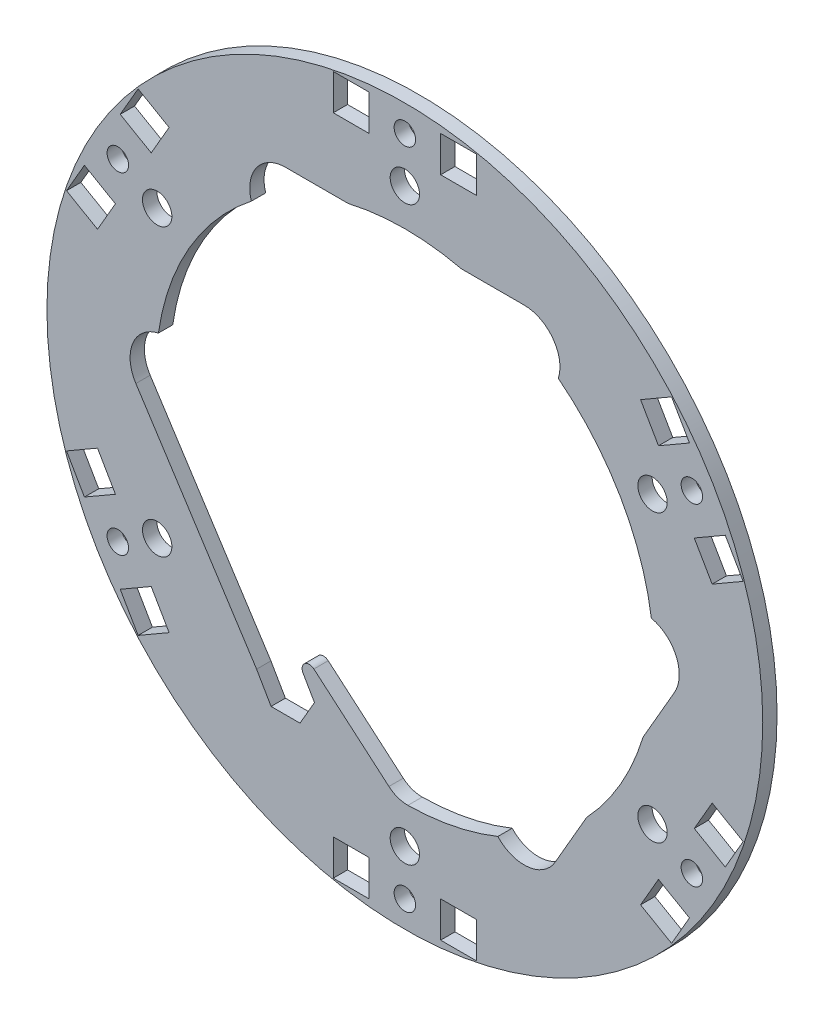
SolidWorks part; units mm, degrees
ref_plane "Plan de face" through (0, 0, 0) normal (0, 0, 1) x (1, 0, 0)
ref_plane "Plan de dessus" through (0, 0, 0) normal (0, 1, 0) x (1, 0, 0)
ref_plane "Plan de droite" through (0, 0, 0) normal (1, 0, 0) x (0, 0, -1)
sketch "Esquisse1" plane through (0, 0, 0) normal (0, 0, 1) x (1, 0, 0)
  line L0 (53.6751, 0) -> (-86.559, 0) construction
  line L1 (0, 50) -> (0, -56.2363) construction
  line L2 (0, 0) -> (70.5826, 40.7509) construction
  line L3 (0, 0) -> (-77.9761, 45.0195) construction
  line L4 (-33.3333, 0) -> (-16.6667, -28.8675) construction
  line L5 (-28.8394, 2.305) -> (-14.6459, -25.3675)
  line L6 (-37.5765, -2.7394) -> (-20.7081, -28.8675)
  line L7 (16.6667, -28.8675) -> (33.3333, 0) construction
  line L8 (12.3365, -26.3675) -> (29.0032, 2.5)
  line L9 (20.9968, -31.3675) -> (37.6635, -2.5)
  line L10 (-16.6667, 28.8675) -> (16.6667, 28.8675) construction
  line L11 (-16.6667, 33.8675) -> (16.6667, 33.8675)
  line L12 (-16.6667, 23.8675) -> (16.6667, 23.8675)
  line L15 (-20.7081, -28.8675) -> (-18.6874, -32.3675)
  line L16 (-18.6874, -32.3675) -> (-14.6459, -32.3675)
  line L17 (-14.6459, -32.3675) -> (-12.6252, -28.8675)
  line L18 (-12.6252, -28.8675) -> (-14.6459, -25.3675)
  line L20 (-14.6459, -25.3675) -> (-18.6874, -25.3675) [skipped]
  line L21 (-18.6874, -25.3675) -> (-20.7081, -28.8675) [skipped]
  circle A0 centre (0, 0) radius 50
  circle A1 centre (33.3333, 0) radius 16.6667 construction
  circle A2 centre (16.6667, -28.8675) radius 16.6667 construction
  circle A3 centre (-16.6667, -28.8675) radius 16.6667 construction
  circle A4 centre (-33.3333, 0) radius 16.6667 construction
  circle A5 centre (-16.6667, 28.8675) radius 16.6667 construction
  circle A6 centre (16.6667, 28.8675) radius 16.6667 construction
  circle A7 centre (-34.5978, 19.9751) radius 2.05
  circle A8 centre (0, 39.9502) radius 2.05
  circle A9 centre (34.5978, 19.9751) radius 2.05
  circle A10 centre (34.5978, -19.9751) radius 2.05
  circle A11 centre (0, -39.9502) radius 2.05
  circle A12 centre (-34.5978, -19.9751) radius 2.05
  circle A13 centre (0, 19.1653) radius 2.05
  circle A14 centre (0, 0) radius 16.6667 construction
  circle A15 centre (0, -19.2328) radius 2.05
  circle A17 centre (-16.6667, -28.8675) radius 3.5 construction
  circle A22 centre (0, 0) radius 2.05
  circle A23 centre (-16.6714, -9.6252) radius 2.05
  circle A24 centre (16.6696, 9.6242) radius 2.05
  circle A25 centre (-16.6714, 9.6252) radius 2.05
  circle A26 centre (16.6667, -9.6225) radius 2.05
  arc A27 (-28.8394, 2.305) -> (-37.5765, -2.7394) centre (-33.3333, 0) ccw
  arc A29 (12.3365, -26.3675) -> (20.9968, -31.3675) centre (16.6667, -28.8675) ccw
  arc A30 (37.6635, -2.5) -> (29.0032, 2.5) centre (33.3333, 0) ccw
  arc A31 (-16.6667, 33.8675) -> (-16.6667, 23.8675) centre (-16.6667, 28.8675) ccw
  arc A32 (16.6667, 23.8675) -> (16.6667, 33.8675) centre (16.6667, 28.8675) ccw
  point P20 (0, 0)
  point P30 (0, 0)
  point P54 (0, 0)
  point P60 (0, 0)
  point P64 (-25, -14.4338)
  point P69 (25, -14.4338)
  point P74 (0, 28.8675)
  line B0 (37.597, -27.4801) -> (42.597, -18.8199) construction
  line B1 (35.4319, -26.2301) -> (32.9319, -30.5603)
  line B2 (35.4319, -26.2301) -> (39.762, -28.7301)
  line B3 (39.762, -28.7301) -> (37.262, -33.0603)
  line B4 (32.9319, -30.5603) -> (37.262, -33.0603)
  line B5 (40.4319, -17.5699) -> (42.9319, -13.2397)
  line B6 (40.4319, -17.5699) -> (44.762, -20.0699)
  line B7 (44.762, -20.0699) -> (47.262, -15.7397)
  line B8 (42.9319, -13.2397) -> (47.262, -15.7397)
  circle B9 centre (40.097, -23.15) radius 1.5
  line B10 (-5, -46.3) -> (5, -46.3) construction
  line B11 (-5, -43.8) -> (-10, -43.8)
  line B12 (-5, -43.8) -> (-5, -48.8)
  line B13 (-5, -48.8) -> (-10, -48.8)
  line B14 (-10, -43.8) -> (-10, -48.8)
  line B15 (5, -43.8) -> (10, -43.8)
  line B16 (5, -43.8) -> (5, -48.8)
  line B17 (5, -48.8) -> (10, -48.8)
  line B18 (10, -43.8) -> (10, -48.8)
  circle B19 centre (0, -46.3) radius 1.5
  line B20 (-42.597, -18.8199) -> (-37.597, -27.4801) construction
  line B21 (-40.4319, -17.5699) -> (-42.9319, -13.2397)
  line B22 (-40.4319, -17.5699) -> (-44.762, -20.0699)
  line B23 (-44.762, -20.0699) -> (-47.262, -15.7397)
  line B24 (-42.9319, -13.2397) -> (-47.262, -15.7397)
  line B25 (-35.4319, -26.2301) -> (-32.9319, -30.5603)
  line B26 (-35.4319, -26.2301) -> (-39.762, -28.7301)
  line B27 (-39.762, -28.7301) -> (-37.262, -33.0603)
  line B28 (-32.9319, -30.5603) -> (-37.262, -33.0603)
  circle B29 centre (-40.097, -23.15) radius 1.5
  line B30 (-37.597, 27.4801) -> (-42.597, 18.8199) construction
  line B31 (-35.4319, 26.2301) -> (-32.9319, 30.5603)
  line B32 (-35.4319, 26.2301) -> (-39.762, 28.7301)
  line B33 (-39.762, 28.7301) -> (-37.262, 33.0603)
  line B34 (-32.9319, 30.5603) -> (-37.262, 33.0603)
  line B35 (-40.4319, 17.5699) -> (-42.9319, 13.2397)
  line B36 (-40.4319, 17.5699) -> (-44.762, 20.0699)
  line B37 (-44.762, 20.0699) -> (-47.262, 15.7397)
  line B38 (-42.9319, 13.2397) -> (-47.262, 15.7397)
  circle B39 centre (-40.097, 23.15) radius 1.5
  line B40 (5, 46.3) -> (-5, 46.3) construction
  line B41 (5, 43.8) -> (10, 43.8)
  line B42 (5, 43.8) -> (5, 48.8)
  line B43 (5, 48.8) -> (10, 48.8)
  line B44 (10, 43.8) -> (10, 48.8)
  line B45 (-5, 43.8) -> (-10, 43.8)
  line B46 (-5, 43.8) -> (-5, 48.8)
  line B47 (-5, 48.8) -> (-10, 48.8)
  line B48 (-10, 43.8) -> (-10, 48.8)
  circle B49 centre (0, 46.3) radius 1.5
  line B50 (42.597, 18.8199) -> (37.597, 27.4801) construction
  line B51 (40.4319, 17.5699) -> (42.9319, 13.2397)
  line B52 (40.4319, 17.5699) -> (44.762, 20.0699)
  line B53 (44.762, 20.0699) -> (47.262, 15.7397)
  line B54 (42.9319, 13.2397) -> (47.262, 15.7397)
  line B55 (35.4319, 26.2301) -> (32.9319, 30.5603)
  line B56 (35.4319, 26.2301) -> (39.762, 28.7301)
  line B57 (39.762, 28.7301) -> (37.262, 33.0603)
  line B58 (32.9319, 30.5603) -> (37.262, 33.0603)
  circle B59 centre (40.097, 23.15) radius 1.5
  dimension "D1" = 6
  dimension "D2" = 30
  dimension "D4" = 6
  dimension "D6" = 46.3
  dimension "D3" = 30
  dimension "D7" = 6
sketch_block_instance "Trou M3 plots 5mm-1"
sketch_block "Trou M3 plots 5mm" parameters "D2"=3, "D1"=5, "D3"=5, "D4"=10
sketch_block_instance "Trou M3 plots 5mm-3"
sketch_block_instance "Trou M3 plots 5mm-4"
sketch_block_instance "Trou M3 plots 5mm-5"
sketch_block_instance "Trou M3 plots 5mm-6"
sketch_block_instance "Trou M3 plots 5mm-7"
extrude "Boss.-Extru.1" add sketch "Esquisse1" along normal blind 2
sketch "Sketch3" plane through (0, 0, 2) normal (0, 0, 1) x (1, 0, 0)
  line L0 (53.6751, 0) -> (-86.559, 0) construction
  line L1 (-11, -4) -> (-10, -4)
  line L2 (-11, -4) -> (-11, 4)
  line L3 (-11, 4) -> (-10, 4)
  line L4 (-10, -4) -> (-10, 4)
  line L5 (0, 50) -> (0, -56.2363) construction
  line L6 (16.6667, 28.8675) -> (-16.6667, -28.8675) construction
  line L7 (-23.3333, 4) -> (-22.3333, 4)
  line L8 (-23.3333, 4) -> (-23.3333, -4)
  line L9 (-23.3333, -4) -> (-22.3333, -4)
  line L10 (-22.3333, 4) -> (-22.3333, -4)
  line L11 (-16.6667, 28.8675) -> (16.6667, -28.8675) construction
  line L12 (-13.2337, 23.9214) -> (-14.0997, 23.4214)
  line L13 (-14.0997, 23.4214) -> (-12.3497, 20.3903)
  line L14 (-12.3497, 20.3903) -> (-15.3808, 18.6403)
  line L15 (-15.3808, 18.6403) -> (-14.8808, 17.7742)
  line L16 (-14.8808, 17.7742) -> (-11.8497, 19.5242)
  line L17 (-11.8497, 19.5242) -> (-10.0997, 16.4932)
  line L18 (-10.0997, 16.4932) -> (-9.2337, 16.9932)
  line L19 (-9.2337, 16.9932) -> (-10.9837, 20.0242)
  line L20 (-10.9837, 20.0242) -> (-7.9526, 21.7742)
  line L21 (-7.9526, 21.7742) -> (-8.4526, 22.6403)
  line L22 (-8.4526, 22.6403) -> (-11.4837, 20.8903)
  line L23 (-11.4837, 20.8903) -> (-13.2337, 23.9214)
  line L24 (-16.2531, 17.5593) -> (-5.3419, 23.8588) construction
  line L25 (-14.6252, 25.3316) -> (-8.4936, 14.7114) construction
  line L26 (15.1308, 18.2073) -> (14.6308, 17.3412)
  line L27 (15.1308, 18.2073) -> (8.2026, 22.2073)
  line L28 (8.2026, 22.2073) -> (7.7026, 21.3412)
  line L29 (14.6308, 17.3412) -> (7.7026, 21.3412)
  line L30 (8.2026, -22.2073) -> (7.7026, -21.3412)
  line L31 (8.2026, -22.2073) -> (15.1308, -18.2073)
  line L32 (15.1308, -18.2073) -> (14.6308, -17.3412)
  line L33 (7.7026, -21.3412) -> (14.6308, -17.3412)
  line L34 (27.3333, -0.5) -> (27.3333, 0.5)
  line L35 (27.3333, 0.5) -> (23.8333, 0.5)
  line L36 (23.8333, 0.5) -> (23.8333, 4)
  line L37 (23.8333, 4) -> (22.8333, 4)
  line L38 (22.8333, 4) -> (22.8333, 0.5)
  line L39 (22.8333, 0.5) -> (19.3333, 0.5)
  line L40 (19.3333, 0.5) -> (19.3333, -0.5)
  line L41 (19.3333, -0.5) -> (22.8333, -0.5)
  line L42 (22.8333, -0.5) -> (22.8333, -4)
  line L43 (22.8333, -4) -> (23.8333, -4)
  line L44 (23.8333, -4) -> (23.8333, -0.5)
  line L45 (23.8333, -0.5) -> (27.3333, -0.5)
  line L46 (-14.0997, -23.4214) -> (-13.2337, -23.9214)
  line L47 (-13.2337, -23.9214) -> (-11.4837, -20.8903)
  line L48 (-11.4837, -20.8903) -> (-8.4526, -22.6403)
  line L49 (-8.4526, -22.6403) -> (-7.9526, -21.7742)
  line L50 (-7.9526, -21.7742) -> (-10.9837, -20.0242)
  line L51 (-10.9837, -20.0242) -> (-9.2337, -16.9932)
  line L52 (-9.2337, -16.9932) -> (-10.0997, -16.4932)
  line L53 (-10.0997, -16.4932) -> (-11.8497, -19.5242)
  line L54 (-11.8497, -19.5242) -> (-14.8808, -17.7742)
  line L55 (-14.8808, -17.7742) -> (-15.3808, -18.6403)
  line L56 (-15.3808, -18.6403) -> (-12.3497, -20.3903)
  line L57 (-12.3497, -20.3903) -> (-14.0997, -23.4214)
  line L58 (-21.8333, 14.2784) -> (-24.4284, 9.7836) construction
  line L59 (173205.0808, -100000) -> (-173283.0568, 100045.0195) construction
  text T0 "+"
  point P4 (-10, 0)
  point P36 (-8.2026, 22.2073)
  point P39 (-13.6667, 23.6714)
  point P51 (0, 0)
  point P75 (0, 0)
  point P85 (-23.3333, 0)
  dimension "D1" = 8
  dimension "D2" = 1
  dimension "D3" = 10
  dimension "D4" = 1
  dimension "D5" = 8
  dimension "D6" = 10
  dimension "D7" = 1
  dimension "D8" = 1
  dimension "D9" = 8
  dimension "D10" = 8
  dimension "D11" = 4
  dimension "D12" = 4
  dimension "D13" = 10
  dimension "D14" = 3
  dimension "D15" = 3
extrude "Cut-Extrude2" cut sketch "Sketch3" against normal blind 10
sketch "Sketch4" plane through (0, 0, 2) normal (0, 0, 1) x (1, 0, 0)
  circle A0 centre (16.6667, -9.6225) radius 9
  circle A1 centre (0, -19.245) radius 9
  circle A2 centre (-16.6667, -9.6225) radius 9
  circle A3 centre (-16.6667, 9.6225) radius 9
  circle A4 centre (0, 19.245) radius 9
  circle A5 centre (16.6667, 9.6225) radius 9
  circle A6 centre (0, 0) radius 9
  point P15 (0, 0)
  dimension "D1" = 6
sketch "Sketch5" plane through (0, 0, 2) normal (0, 0, 1) x (1, 0, 0)
  line L3 (-16.6429, -21.474) -> (-1.1196, -34.7596)
  line L5 (-14.6459, -25.3675) -> (-28.8394, 2.305) construction
  line L6 (-16.6429, -21.474) -> (-34.4263, 4.9309)
  arc A1 (-1.1196, -34.7596) -> (-34.4263, 4.9309) centre (0, 0) ccw
  arc A2 (-28.8394, 2.305) -> (-37.5765, -2.7394) centre (-33.3333, 0) ccw construction
extrude "Cut-Extrude5" cut sketch "Sketch5" against normal blind 10
fillet "Fillet1" radius 1 1 edges at (-16.6429, -21.474, 1)
fillet "Fillet2" radius 4 1 edges at (-1.1196, -34.7596, 1)
